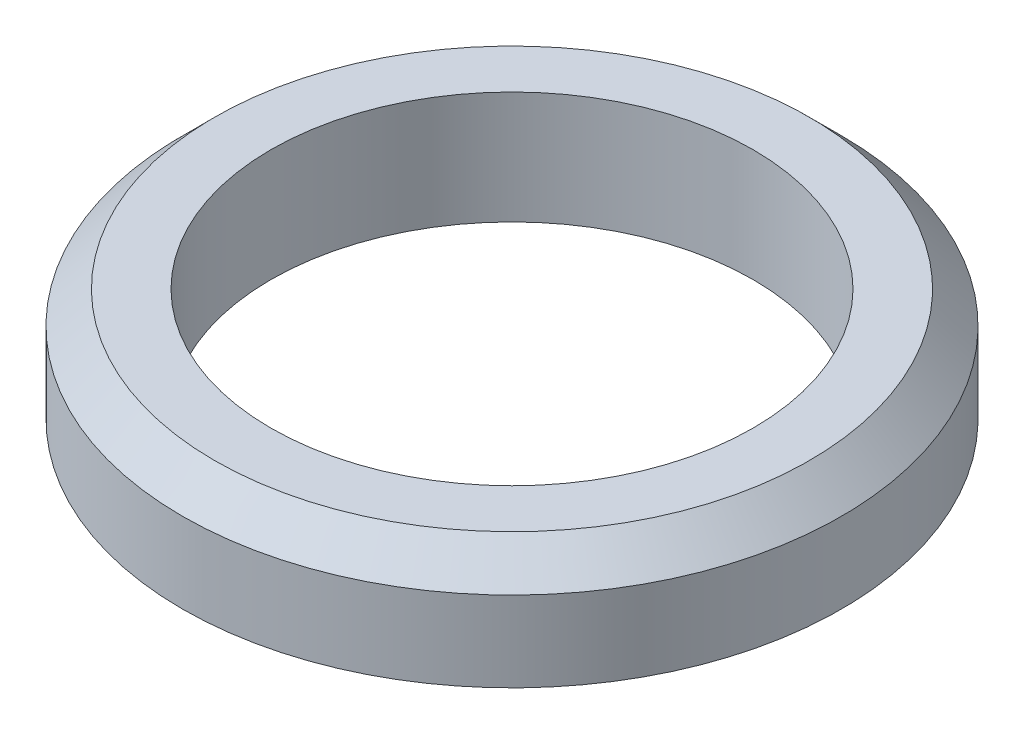
SolidWorks part; units mm, degrees
ref_plane "Front Plane" through (0, 0, 0) normal (0, 0, 1) x (1, 0, 0)
ref_plane "Top Plane" through (0, 0, 0) normal (0, 1, 0) x (1, 0, 0)
ref_plane "Right Plane" through (0, 0, 0) normal (1, 0, 0) x (0, 0, -1)
sketch "Sketch1" plane through (0, 0, 0) normal (0, 1, 0) x (1, 0, 0)
  circle A0 centre (0, 0) radius 20.5
  circle A1 centre (0, 0) radius 15
  dimension "D1" = 41
  dimension "D2" = 30
extrude "Boss-Extrude1" add sketch "Sketch1" along normal blind 7
chamfer "Chamfer1" distance 2 angle 45 1 edges at (0, 7, 20.5)
